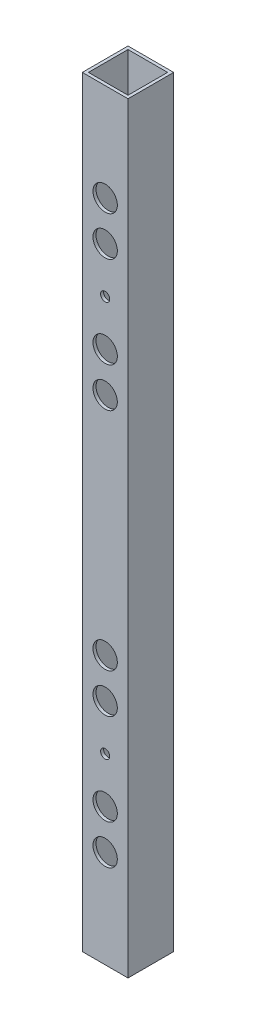
SolidWorks part; units mm, degrees
ref_plane "前视基准面" through (0, 0, 0) normal (0, 0, 1) x (1, 0, 0)
ref_plane "上视基准面" through (0, 0, 0) normal (0, 1, 0) x (1, 0, 0)
ref_plane "右视基准面" through (0, 0, 0) normal (1, 0, 0) x (0, 0, -1)
sketch "草图1" plane through (0, 0, 0) normal (0, 1, 0) x (1, 0, 0)
  line L0 (-6.5, 6.5) -> (6.5, 6.5)
  line L1 (-7.5, -7.5) -> (7.5, -7.5)
  line L2 (-7.5, -7.5) -> (-7.5, 7.5)
  line L3 (-7.5, 7.5) -> (7.5, 7.5)
  line L4 (7.5, -7.5) -> (7.5, 7.5)
  line L5 (-7.5, -7.5) -> (7.5, 7.5) construction
  line L6 (-7.5, 7.5) -> (7.5, -7.5) construction
  line L7 (6.5, -6.5) -> (6.5, 6.5)
  line L8 (-6.5, -6.5) -> (6.5, -6.5)
  line L9 (-6.5, -6.5) -> (-6.5, 6.5)
  point P0 (0, 0)
  dimension "D1" = 15
  dimension "D2" = 15
  dimension "D3" = 1
extrude "凸台-拉伸1" add sketch "草图1" along normal blind 250
sketch "草图2" plane through (0, 0, -7.5) normal (0, 0, -1) x (-1, 0, 0)
  line L0 (-15.878, 125) -> (27.9713, 125) construction
  line L1 (-7.5, 250) -> (-7.5, 0) construction
  circle A0 centre (0, 190) radius 1.5
  circle A1 centre (0, 205) radius 1.5
  circle A2 centre (0, 218) radius 1.5
  circle A3 centre (0, 175) radius 1.5
  circle A4 centre (0, 162) radius 1.5
  circle A5 centre (0, 88) radius 1.5
  circle A6 centre (0, 75) radius 1.5
  circle A7 centre (0, 32) radius 1.5
  circle A8 centre (0, 45) radius 1.5
  circle A9 centre (0, 60) radius 1.5
  point P14 (-7.5, 125)
  dimension "D1" = 3
  dimension "D2" = 3
  dimension "D3" = 3
  dimension "D4" = 3
  dimension "D5" = 3
  dimension "D6" = 13
  dimension "D7" = 15
  dimension "D8" = 15
  dimension "D9" = 13
  dimension "D10" = 65
  dimension "D11" = 0
extrude "切除-拉伸1" cut sketch "草图2" against normal blind 250
sketch "草图3" plane through (0, 0, -7.5) normal (0, 0, -1) x (-1, 0, 0)
  circle A0 centre (0, 60) radius 4
  circle A1 centre (0, 190) radius 4
extrude "切除-拉伸2" cut sketch "草图3" against normal blind 2
sketch "草图4" plane through (0, 0, 7.5) normal (0, 0, 1) x (1, 0, 0)
  line L0 (-15.4622, 125) -> (20.458, 125) construction
  circle A0 centre (0, 218) radius 4
  circle A1 centre (0, 205) radius 4
  circle A2 centre (0, 175) radius 4
  circle A3 centre (0, 162) radius 4
  circle A4 centre (0, 88) radius 4
  circle A5 centre (0, 75) radius 4
  circle A6 centre (0, 45) radius 4
  circle A7 centre (0, 32) radius 4
extrude "切除-拉伸3" cut sketch "草图4" against normal blind 2
